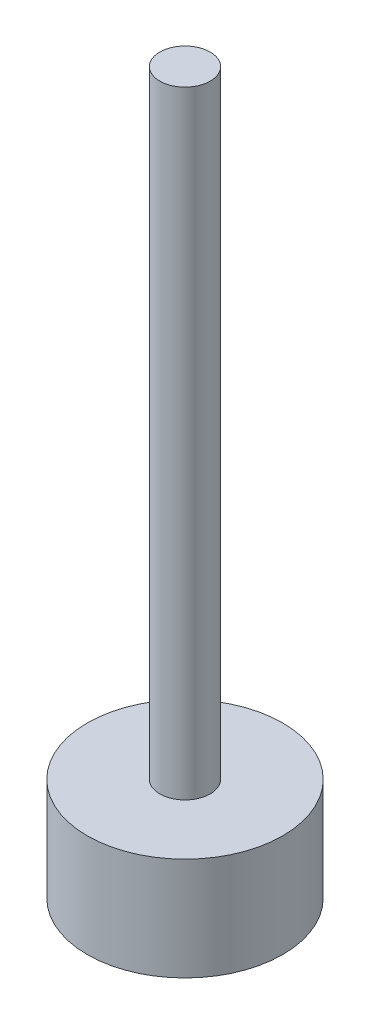
SolidWorks part; units mm, degrees
ref_plane "Front Plane" through (0, 0, 0) normal (0, 0, 1) x (1, 0, 0)
ref_plane "Top Plane" through (0, 0, 0) normal (0, 1, 0) x (1, 0, 0)
ref_plane "Right Plane" through (0, 0, 0) normal (1, 0, 0) x (0, 0, -1)
sketch "Sketch1" plane through (0, 0, 0) normal (0, 1, 0) x (1, 0, 0)
  circle A0 centre (0, 0) radius 12.065
  dimension "D1" = 24.13
extrude "Boss-Extrude1" add sketch "Sketch1" along normal blind 12.7
sketch "Sketch2" plane through (0, 12.7, 0) normal (0, 1, 0) x (1, 0, 0)
  circle A0 centre (0, 0) radius 3.1115
  dimension "D1" = 6.223
extrude "Boss-Extrude2" add sketch "Sketch2" along normal blind 76.2
